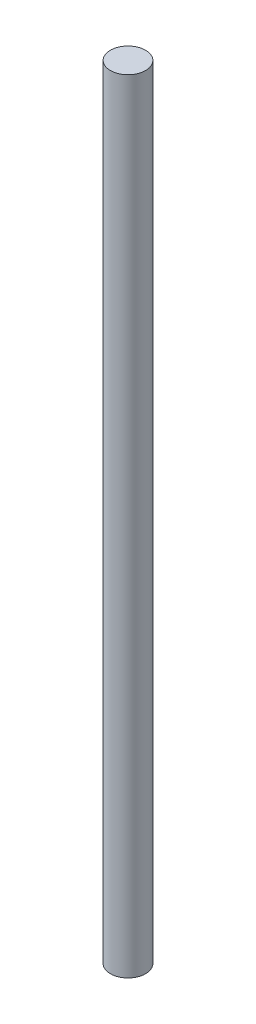
SolidWorks part; units mm, degrees
ref_plane "Front Plane" through (0, 0, 0) normal (0, 0, 1) x (1, 0, 0)
ref_plane "Top Plane" through (0, 0, 0) normal (0, 1, 0) x (1, 0, 0)
ref_plane "Right Plane" through (0, 0, 0) normal (1, 0, 0) x (0, 0, -1)
sketch "Sketch1" plane through (0, 0, 0) normal (0, 0, 1) x (1, 0, 0)
  line L0 (0, 0) -> (0, 300)
  point P6 (0, 300)
  dimension "D2" = 300
sketch "Sketch2" plane through (0, 0, 0) normal (0, 1, 0) x (1, 0, 0)
  circle A0 centre (0, 0) radius 6.75
  dimension "D1" = 13.5
sweep "Sweep1" add profiles "Sketch2" path "Sketch1"
